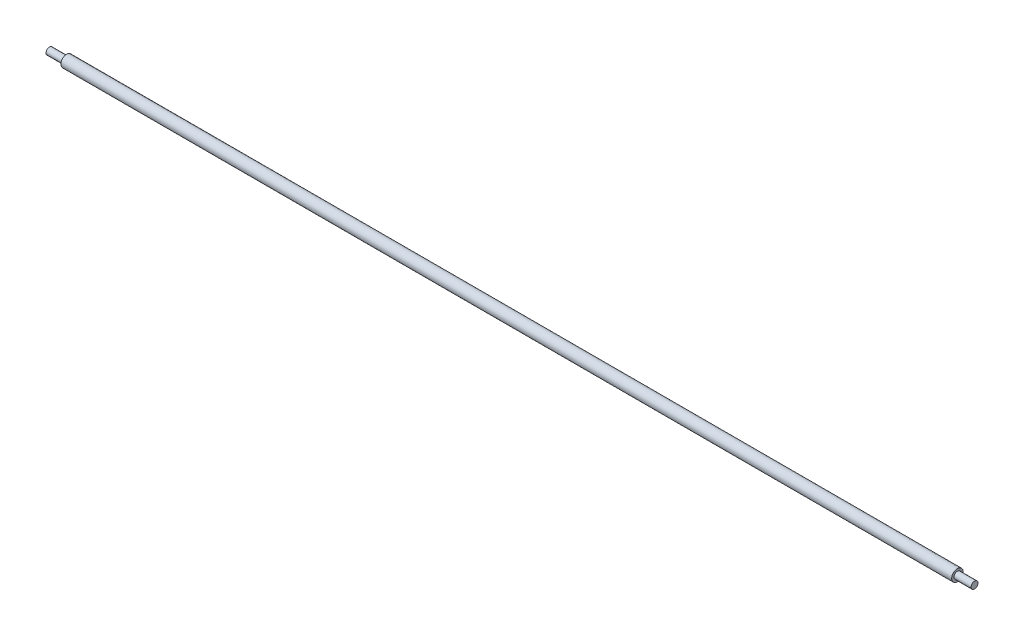
SolidWorks part; units mm, degrees
ref_plane "Спереди" through (0, 0, 0) normal (0, 0, 1) x (1, 0, 0)
ref_plane "Сверху" through (0, 0, 0) normal (0, 1, 0) x (1, 0, 0)
ref_plane "Справа" through (0, 0, 0) normal (1, 0, 0) x (0, 0, -1)
sketch "Эскиз1" plane through (0, 0, 0) normal (1, 0, 0) x (0, 0, -1)
  circle A0 centre (0, 0) radius 5
  dimension "D1" = 10
extrude "Бобышка-Вытянуть1" add sketch "Эскиз1" along normal blind 508 and the other way blind 270
sketch "Эскиз2" plane through (-270, 0, 0) normal (-1, 0, 0) x (0, 0, 1)
  circle A0 centre (0, 0) radius 3
  dimension "D1" = 6
extrude "Бобышка-Вытянуть2" add sketch "Эскиз2" along normal blind 15
cosmetic thread "Условное изображение резьбы4" parameters "D1"=14.9999, "D2"=4.891
sketch "Эскиз7" plane through (508, 0, 0) normal (1, 0, 0) x (0, 0, -1)
  circle A0 centre (0, 0) radius 3
  dimension "D1" = 6
extrude "Бобышка-Вытянуть3" add sketch "Эскиз7" along normal blind 15
cosmetic thread "Условное изображение резьбы5" parameters "D1"=14.9999, "D2"=4.891
